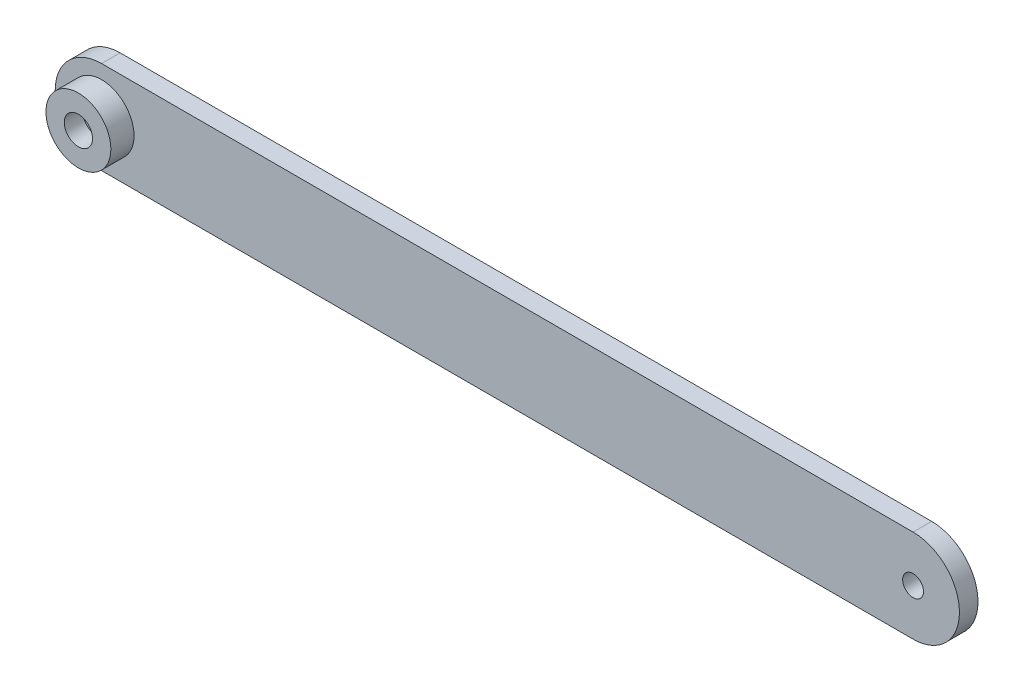
SolidWorks part; units mm, degrees
material "PET"
ref_plane "Front Plane" through (0, 0, 0) normal (0, 0, 1) x (1, 0, 0)
ref_plane "Top Plane" through (0, 0, 0) normal (0, 1, 0) x (1, 0, 0)
ref_plane "Right Plane" through (0, 0, 0) normal (1, 0, 0) x (0, 0, -1)
sketch "Sketch1" plane through (0, 0, 0) normal (0, 0, 1) x (1, 0, 0)
  line L0 (0, 0) -> (175, 0) construction
  line L1 (0, 10) -> (175, 10)
  line L2 (0, -10) -> (175, -10)
  arc A0 (0, 10) -> (0, -10) centre (0, 0) ccw
  arc A1 (175, -10) -> (175, 10) centre (175, 0) ccw
  circle A3 centre (175, 0) radius 2.25
  circle A9 centre (0, 0) radius 1
  point P3 (87.5, 0)
  dimension "D1" = 10
  dimension "D3" = 4.5
  dimension "D4" = 2
  dimension "D2" = 175
extrude "Boss-Extrude1" add sketch "Sketch1" along normal mid plane 4
sketch "Sketch4" plane through (0, 0, 2) normal (0, 0, 1) x (1, 0, 0)
  circle A0 centre (0, 0) radius 7
  circle A1 centre (0, 0) radius 1 construction
  circle A2 centre (0, 0) radius 1
  dimension "D1" = 14
extrude "Boss-Extrude2" add sketch "Sketch4" along normal blind 1
sketch "Sketch5" plane through (0, 0, 3) normal (0, 0, 1) x (1, 0, 0)
  circle A0 centre (0, 0) radius 7 construction
  circle A1 centre (0, 0) radius 7
  circle A2 centre (0, 0) radius 3.05
  dimension "D1" = 6.1
extrude "Boss-Extrude3" add sketch "Sketch5" along normal blind 4
sketch "Sketch6" plane through (0, 0, -2) normal (0, 0, -1) x (-1, 0, 0)
  line L0 (0, 2.0758) -> (0, 2.375) construction
  line L1 (-0.3247, 2.0503) -> (0, 2.375)
  line L2 (0.3247, 2.0503) -> (0, 2.375)
  line L3 (0.3247, 2.0503) -> (0.7339, 2.2588)
  line L4 (0.9424, 1.8496) -> (0.7339, 2.2588)
  line L5 (0.9424, 1.8496) -> (1.396, 1.9214)
  line L6 (1.4678, 1.4678) -> (1.396, 1.9214)
  line L7 (1.4678, 1.4678) -> (1.9214, 1.396)
  line L8 (1.8496, 0.9424) -> (1.9214, 1.396)
  line L9 (1.8496, 0.9424) -> (2.2588, 0.7339)
  line L10 (2.0503, 0.3247) -> (2.2588, 0.7339)
  line L11 (2.0503, 0.3247) -> (2.375, 0)
  line L12 (2.0503, -0.3247) -> (2.375, 0)
  line L13 (2.0503, -0.3247) -> (2.2587, -0.7339)
  line L14 (1.8496, -0.9424) -> (2.2587, -0.7339)
  line L15 (1.8496, -0.9424) -> (1.9214, -1.396)
  line L16 (1.4678, -1.4678) -> (1.9214, -1.396)
  line L17 (1.4678, -1.4678) -> (1.396, -1.9214)
  line L18 (0.9424, -1.8496) -> (1.396, -1.9214)
  line L19 (0.9424, -1.8496) -> (0.7339, -2.2588)
  line L20 (0.3247, -2.0503) -> (0.7339, -2.2588)
  line L21 (0.3247, -2.0503) -> (0, -2.375)
  line L22 (-0.3247, -2.0503) -> (0, -2.375)
  line L23 (-0.3247, -2.0503) -> (-0.7339, -2.2588)
  line L24 (-0.9424, -1.8496) -> (-0.7339, -2.2588)
  line L25 (-0.9424, -1.8496) -> (-1.396, -1.9214)
  line L26 (-1.4678, -1.4678) -> (-1.396, -1.9214)
  line L27 (-1.4678, -1.4678) -> (-1.9214, -1.396)
  line L28 (-1.8496, -0.9424) -> (-1.9214, -1.396)
  line L29 (-1.8496, -0.9424) -> (-2.2588, -0.7339)
  line L30 (-2.0503, -0.3247) -> (-2.2588, -0.7339)
  line L31 (-2.0503, -0.3247) -> (-2.375, 0)
  line L32 (-2.0503, 0.3247) -> (-2.375, 0)
  line L33 (-2.0503, 0.3247) -> (-2.2588, 0.7339)
  line L34 (-1.8496, 0.9424) -> (-2.2588, 0.7339)
  line L35 (-1.8496, 0.9424) -> (-1.9214, 1.396)
  line L36 (-1.4678, 1.4678) -> (-1.9214, 1.396)
  line L37 (-1.4678, 1.4678) -> (-1.396, 1.9214)
  line L38 (-0.9424, 1.8496) -> (-1.396, 1.9214)
  line L39 (-0.9424, 1.8496) -> (-0.7339, 2.2588)
  line L40 (-0.3247, 2.0503) -> (-0.7339, 2.2588)
  circle A0 centre (0, 0) radius 2.375 construction
  circle A1 centre (0, 0) radius 2.0758 construction
  circle A3 centre (0, 0) radius 1 construction
  point P9 (0, 0)
  point P10 (-5.1361, -1.146)
  point P11 (2.2488, -0.9209)
  point P14 (0, 0)
  point P17 (-0.7339, 2.375)
  point P20 (1.4678, 1.8496)
  point P23 (0, 0)
  point P26 (0, 0)
  point P29 (0, 0)
  point P38 (0, 0)
  point P41 (0.7339, 2.375)
  point P44 (0, 2.0503)
  point P67 (0, 0)
  dimension "D1" = 20
  dimension "D2" = 4.75
  dimension "D3" = 45
extrude "Cut-Extrude1" cut sketch "Sketch6" against normal blind 3
